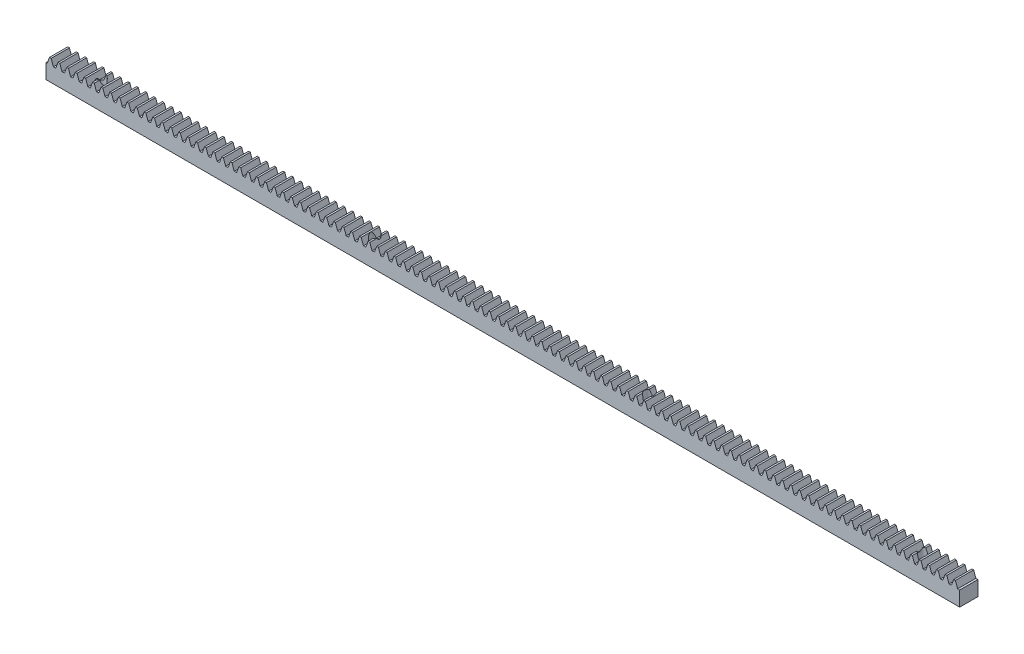
SolidWorks part; units mm, degrees
extrude "Blank" add sketch "BlankSke" against normal blind 20
sketch "BlankSke" plane through (0, 0, 0) normal (0, 0, 1) x (1, 0, 0)
  line L1 (0, 0) -> (1000, 0)
  line L2 (0, 0) -> (0, 23)
  line L3 (0, 23) -> (1000, 23)
  line L4 (1000, 0) -> (1000, 23)
  dimension "Length" = 1000
  dimension "Blank_height" = 23
ref_plane "Plane1" through (0, 0, 0) normal (0, 0, 1) x (1, 0, 0)
ref_plane "Plane2" through (0, 0, 0) normal (0, 1, 0) x (1, 0, 0)
ref_plane "Plane3" through (0, 0, 0) normal (1, 0, 0) x (0, 0, -1)
sketch "HoldingSke" plane through (0, 0, 0) normal (0, 1, 0) x (1, 0, 0)
  line L0 (0, 0) -> (0.0464, 0.3301)
  line L1 (-15, 0) -> (100, 0) construction
  line L2 (0, 0) -> (-2.1039, 2.3779)
  line L3 (0, 0) -> (-11.863, 4.5341)
  line L4 (0, 0) -> (-2.6687, 8.2133)
  line L5 (0, 0) -> (-23.7986, -8.8762)
  line L6 (0, 0) -> (-10.5278, -7.1032)
  line L9 (-71.009, 38.7566) -> (868.6837, 380.7768)
  line L10 (-76.2, 5.3779) -> (-46.2, 5.3779)
  line L11 (0, 0) -> (-20, 0)
  line L12 (-76.2, 101.6) -> (-76.093, 101.6)
  line L13 (24.9733, 27.94) -> (52.9518, 28.4284)
  line L14 (24.9733, 27.94) -> (24.9743, 27.94)
  line L15 (24.9733, 27.94) -> (100.4006, 29.5858)
  circle A0 centre (0, 0) radius 19.05
  circle A1 centre (0, 0) radius 15
  circle A2 centre (0, 0) radius 12.7
  dimension "MPH" = 30
  dimension "Diameter" = 38.1
  dimension "Num_teeth" = 108
  dimension "Pitch" = 0.3333
  dimension "Show_teeth" = 998
  dimension "Thickness" = 12.7
  dimension "Ap" = 20
  dimension "Pitch_height" = 30
  dimension "Width" = 20
  dimension "Backlash" = 0.107
  dimension "Addendum_fac" = 1
  dimension "Dedendum_fac" = 1.25
  dimension "Clearance_fac" = 0.25
  dimension "Dedendum_add" = 0.001
  dimension "Length" = 1000
  dimension "Module" = 3
sketch "TooCutSkeIll" plane through (0, 0, 0) normal (0, 0, 1) x (1, 0, 0)
  line L0 (-0.1007, 22.921) -> (-1.4922, 26.7441)
  line L1 (-0.7865, 26.25) -> (0.7865, 26.25)
  line L2 (1.4922, 26.7441) -> (0.1007, 22.921)
  line L3 (1000, 23) -> (0, 23) construction
  line L4 (0, 0) -> (0, 64.897) construction
  line L5 (-13.208, 30) -> (12.954, 30) construction
  line L6 (0, 0) -> (1000, 0) construction
  line L7 (2.6772, 30) -> (2.6772, 48.7463) construction
  line L8 (-2.6772, 30) -> (-2.6772, 48.7463) construction
  line L9 (0.2134, 23) -> (0.2134, 33.0254)
  line L10 (-0.2134, 23) -> (-0.2134, 33.0254)
  line L11 (-0.2134, 33.0254) -> (0.2134, 33.0254)
  arc A0 (0.7865, 26.25) -> (1.4922, 26.7441) centre (0.7865, 27.001) ccw
  arc A1 (-1.4922, 26.7441) -> (-0.7865, 26.25) centre (-0.7865, 27.001) ccw
  arc A2 (0.2134, 23) -> (0.1007, 22.921) centre (0.2134, 22.88) ccw
  arc A3 (-0.1007, 22.921) -> (-0.2134, 23) centre (-0.2134, 22.88) ccw
  dimension "Pitch_height" = 30
  dimension "Addendum_plus" = 3.0254
  dimension "Pressure_angle" = 20
  dimension "Gap_width" = 5.3544
  dimension "Dedendum" = 3.75
extrude "ToothCutIll" [suppressed] cut sketch "TooCutSkeIll" against normal through all
sketch "TooCutSkeSim" plane through (0, 0, 0) normal (0, 0, 1) x (1, 0, 0)
  line L0 (1.3123, 16.25) -> (-1.3123, 16.25)
  line L1 (3.7784, 23.0254) -> (1.3123, 16.25)
  line L2 (0, 17.4625) -> (0, 53.467) construction
  line L3 (3.7784, 23.0254) -> (-3.7784, 23.0254)
  line L6 (-3.7784, 23.0254) -> (-1.3123, 16.25)
  line L9 (-2.6772, 20) -> (2.6772, 20) construction
  line L10 (0, 0) -> (1000, 0) construction
  line L11 (2.6772, 20) -> (2.6772, 53.467) construction
  line L12 (-2.6772, 20) -> (-2.6772, 53.467) construction
  dimension "Addendum_plus" = 3.0254
  dimension "Pitch_height" = 20
  dimension "Pressure_angle" = 20
  dimension "Gap_width" = 5.3544
  dimension "Dedendum" = 3.75
extrude "ToothCutSim" cut sketch "TooCutSkeSim" against normal through all
pattern_linear "TeethCuts" count 107 spacing 9.4248 along (1, 0, 0) of "ToothCutIll", "ToothCutSim"
sketch "草图1" plane through (0, 0, 0) normal (0, -1, 0) x (1, 0, 0)
  line L0 (0, -20) -> (0, 0) construction
  line L1 (1000, -20) -> (1000, 0) construction
  circle A0 centre (50, -10) radius 2.5
  circle A1 centre (350, -10) radius 2.5
  circle A2 centre (650, -10) radius 2.5
  circle A3 centre (950, -10) radius 2.5
  point P6 (0, -10)
  point P8 (0, 0)
  point P14 (1000, -10)
  point P15 (925.3705, -10)
  point P16 (937.189, -10)
  dimension "D1" = 5
  dimension "D2" = 50
  dimension "D4" = 50
  dimension "D3" = 4
extrude "切除-拉伸1" cut sketch "草图1" against normal through all
ref_plane "基准面1" through (0, 40, 0) normal (0, -1, 0) x (-1, 0, 0)
sketch "草图2" plane through (0, 40, 0) normal (0, -1, 0) x (-1, 0, 0)
  line L0 (0, 20) -> (0, 0) construction
  circle A0 centre (-950, 10) radius 5
  circle A1 centre (-650, 10) radius 5
  circle A2 centre (-350, 10) radius 5
  circle A3 centre (-50, 10) radius 5
  dimension "D1" = 10
  dimension "D3" = 50
  dimension "D2" = 4
extrude "切除-拉伸3" cut sketch "草图2" along normal blind 30
equation "' \"Module@HoldingSke\" = 6.35"
equation "' \"Num_teeth@HoldingSke\" = 12"
equation "' \"Ap@HoldingSke\" =  20"
equation "' \"Ap@HoldingSke\" = 20"
equation "' \"Width@HoldingSke\" = 0.25 * 25.4"
equation "' \"Show_teeth@HoldingSke\" = 500"
equation "' \"Backlash@HoldingSke\" = 0.009 * 25.4"
equation "' \"Addendum_fac@HoldingSke\" = 1.0"
equation "' \"Dedendum_fac@HoldingSke\" = 1.25"
equation "' \"Dedendum_add@HoldingSke\" = 0.00005 * 25.4"
equation "' \"Clearance_fac@HoldingSke\" = 0.25"
equation "' \"Pitch_height@HoldingSke\" = 1 * 25.4"
equation "' \"Length@HoldingSke\" = 4.71 * 25.4"
equation "\"Pitch@HoldingSke\" = 1 / \"Module@HoldingSke\""
equation "\"MPH@HoldingSke\" = \"Dedendum_fac@HoldingSke\" / \"Pitch@HoldingSke\" + 2 * \"Dedendum_add@HoldingSke\" + 0.002 * 25.4"
equation "\"MPH@HoldingSke\" = ((sgn( \"MPH@HoldingSke\" - \"Pitch_height@HoldingSke\")+1)*( \"MPH@HoldingSke\" - \"Pitch_height@HoldingSke\"))/2 + \"Pitch_height@HoldingSke\""
equation "\"Length@BlankSke\" =  \"Length@HoldingSke\""
equation "\"Face_width@Blank\" = \"Width@HoldingSke\""
equation "\"Pressure_angle@TooCutSkeIll\" = \"Ap@HoldingSke\""
equation "\"Addendum_plus@TooCutSkeIll\" =  \"Addendum_fac@HoldingSke\"  / \"Pitch@HoldingSke\" + 0.001 *25.4"
equation "\"Dedendum@TooCutSkeIll\" = \"Dedendum_fac@HoldingSke\"  / \"Pitch@HoldingSke\""
equation "\"Pitch_height@TooCutSkeIll\" =  \"MPH@HoldingSke\""
equation "\"Gap_width@TooCutSkeIll\" = 3.14159265 / 2 / \"Pitch@HoldingSke\" + 6 * \"Backlash@HoldingSke\""
equation "\"Pressure_angle@TooCutSkeSim\" = \"Ap@HoldingSke\""
equation "\"Addendum_plus@TooCutSkeSim\" =  \"Addendum_fac@HoldingSke\"  / \"Pitch@HoldingSke\" + 0.001 * 25.4"
equation "\"Dedendum@TooCutSkeSim\" = \"Dedendum_fac@HoldingSke\"  / \"Pitch@HoldingSke\""
equation "\"Gap_width@TooCutSkeSim\" = 3.14159265 / 2 / \"Pitch@HoldingSke\" + 6 * \"Backlash@HoldingSke\""
equation "\"Root_fillet@TooCutSkeIll\" = \"Clearance_fac@HoldingSke\" / \"Pitch@HoldingSke\" + \"Dedendum_add@HoldingSke\""
equation "\"Break_rad@TooCutSkeIll\" = 0.02 / \"Pitch@HoldingSke\" * 2"
equation "\"Linear_pitch@TeethCuts\" = 3.14159265 / \"Pitch@HoldingSke\""
equation "\"Num_teeth@HoldingSke\" = int( ( \"Length@HoldingSke\" + 0 ) / (3.14159265 / \"Pitch@HoldingSke\")) + 0.9999  + 1"
equation " \"Num_teeth@TeethCuts\" = int( \"Show_teeth@HoldingSke\" ) + 1"
equation " \"Num_teeth@TeethCuts\" = ((sgn( \"Num_teeth@TeethCuts\" - \"Num_teeth@HoldingSke\" )-1)*( \"Num_teeth@TeethCuts\" - \"Num_teeth@HoldingSke\" ))/-2+ \"Num_teeth@HoldingSke\""
equation " \"Num_teeth@TeethCuts\" = ((sgn( \"Num_teeth@TeethCuts\" - 2.0)+1)*( \"Num_teeth@TeethCuts\" - 2.0))/2 +2.0"
